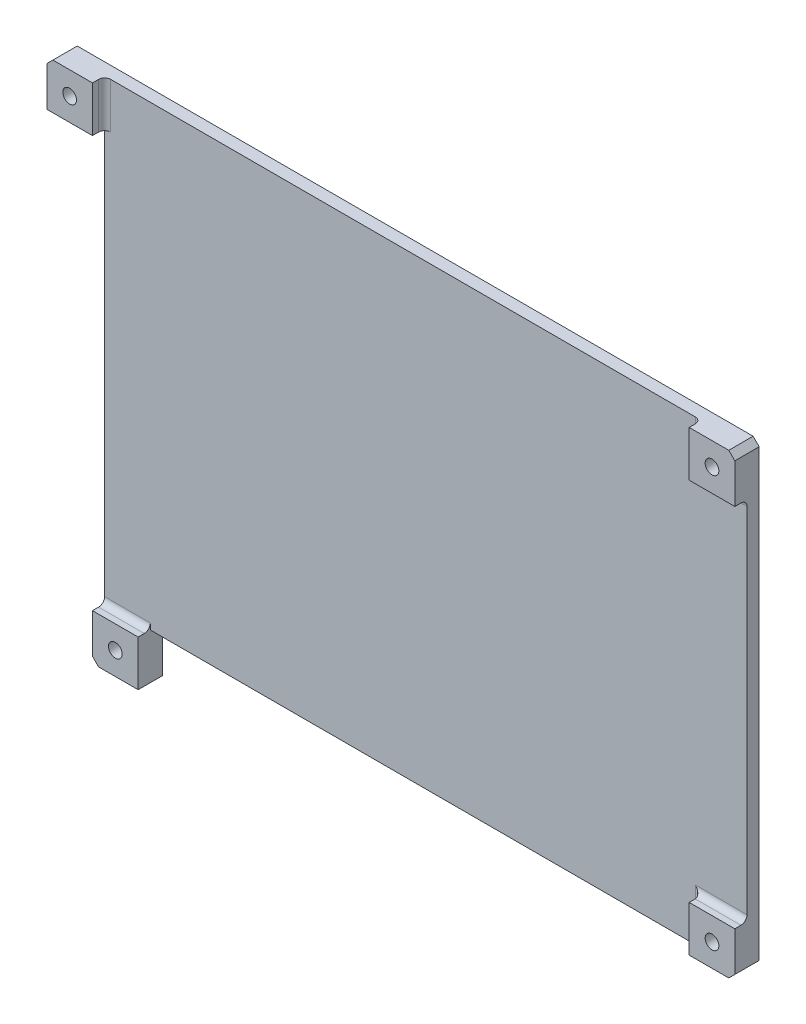
SolidWorks part; units mm, degrees
ref_plane "Front Plane" through (0, 0, 0) normal (0, 0, 1) x (1, 0, 0)
ref_plane "Top Plane" through (0, 0, 0) normal (0, 1, 0) x (1, 0, 0)
ref_plane "Right Plane" through (0, 0, 0) normal (1, 0, 0) x (0, 0, -1)
sketch "Sketch1" plane through (0, 0, 0) normal (0, 0, 1) x (1, 0, 0)
  line L1 (-43.4412, 24.5025) -> (62.0588, 24.5025)
  line L2 (-43.4412, 24.5025) -> (-43.4412, -50.5575)
  line L3 (-43.4412, -50.5575) -> (62.0588, -50.5575)
  line L4 (62.0588, 24.5025) -> (62.0588, -50.5575)
  dimension "D1" = 105.5
  dimension "D2" = 75.06
extrude "Boss-Extrude1" add sketch "Sketch1" along normal blind 2
sketch "Sketch2" plane through (0, 0, 2) normal (0, 0, 1) x (1, 0, 0)
  line L0 (-43.4412, -13.0275) -> (62.0588, -13.0275) construction
  line L1 (-43.4412, 24.5025) -> (-43.4412, -50.5575) construction
  line L2 (62.0588, -50.5575) -> (62.0588, 24.5025) construction
  line L3 (54.5588, -43.0575) -> (62.0588, -43.0575)
  line L4 (54.5588, 24.5025) -> (62.0588, 24.5025)
  line L5 (54.5588, 24.5025) -> (54.5588, 17.0025)
  line L6 (54.5588, 17.0025) -> (62.0588, 17.0025)
  line L7 (62.0588, 24.5025) -> (62.0588, 17.0025)
  line L8 (62.0588, -50.5575) -> (62.0588, -43.0575)
  line L9 (54.5588, -50.5575) -> (62.0588, -50.5575)
  line L10 (54.5588, -50.5575) -> (54.5588, -43.0575)
  circle A0 centre (58.3088, 20.7525) radius 1.125
  point P12 (0, 0)
  dimension "D1" = 2.25
  dimension "D4" = 3.75
  dimension "D5" = 3.75
  dimension "D2" = 7.5
  dimension "D3" = 7.5
extrude "Boss-Extrude2" add sketch "Sketch2" along normal blind 2
sketch "Sketch3" plane through (0, 0, 2) normal (0, 0, 1) x (1, 0, 0)
  circle A0 centre (58.3088, 20.7525) radius 1.125
  circle A1 centre (58.3088, 20.7525) radius 1.125 construction
  circle A2 centre (58.3088, 20.7525) radius 1.125 construction
extrude "Cut-Extrude1" cut sketch "Sketch3" against normal blind 4
sketch "Sketch4" plane through (0, 0, 4) normal (0, 0, 1) x (1, 0, 0)
  line L0 (62.0588, -43.0575) -> (54.5588, -43.0575) construction
  line L1 (54.5588, -43.0575) -> (54.5588, -50.5575) construction
  circle A0 centre (58.3088, -46.8075) radius 1.125
  dimension "D1" = 2.25
  dimension "D2" = 3.75
  dimension "D3" = 3.75
extrude "Cut-Extrude2" cut sketch "Sketch4" against normal blind 4
sketch "Sketch5" plane through (0, 0, 2) normal (0, 0, 1) x (1, 0, 0)
  line L1 (-50.9412, 24.5025) -> (-43.4412, 24.5025)
  line L2 (-50.9412, 24.5025) -> (-50.9412, 17.0025)
  line L3 (-50.9412, 17.0025) -> (-43.4412, 17.0025)
  line L4 (-43.4412, 24.5025) -> (-43.4412, 17.0025)
  point P4 (0, 0)
  dimension "D1" = 7.5
  dimension "D2" = 7.5
extrude "Boss-Extrude3" add sketch "Sketch5" along normal mid plane 4
sketch "Sketch6" plane through (0, 0, 4) normal (0, 0, 1) x (1, 0, 0)
  line L0 (-43.4412, 24.5025) -> (-50.9412, 24.5025) construction
  line L1 (-50.9412, 24.5025) -> (-50.9412, 17.0025) construction
  circle A0 centre (-47.1912, 20.7525) radius 1.125
  dimension "D1" = 2.25
  dimension "D2" = 3.75
  dimension "D3" = 3.75
extrude "Cut-Extrude3" cut sketch "Sketch6" against normal blind 4
sketch "Sketch7" plane through (0, 0, 2) normal (0, 0, 1) x (1, 0, 0)
  line L1 (-35.9412, -58.0575) -> (-43.4412, -58.0575)
  line L2 (-35.9412, -58.0575) -> (-35.9412, -50.5575)
  line L3 (-35.9412, -50.5575) -> (-43.4412, -50.5575)
  line L4 (-43.4412, -58.0575) -> (-43.4412, -50.5575)
  point P4 (-14.8384, -6.9774)
  point P5 (0, 0)
  dimension "D1" = 7.5
  dimension "D2" = 7.5
extrude "Boss-Extrude4" add sketch "Sketch7" along normal mid plane 4
sketch "Sketch8" plane through (0, 0, 4) normal (0, 0, 1) x (1, 0, 0)
  line L1 (-43.4412, -58.0575) -> (-35.9412, -58.0575) construction
  line L2 (-35.9412, -58.0575) -> (-35.9412, -50.5575) construction
  circle A0 centre (-39.6912, -54.3075) radius 1.125
  dimension "D1" = 2.25
  dimension "D2" = 3.75
  dimension "D3" = 3.75
extrude "Cut-Extrude4" cut sketch "Sketch8" against normal blind 4
fillet "Fillet2" radius 1 2 edges at (-39.6912, -50.5575, 2) (-43.4412, 20.7525, 2)
fillet "Fillet3" radius 1 4 edges at (58.3088, 17.0025, 2) (54.5588, 20.7525, 2) (54.5588, -46.8075, 2) (58.3088, -43.0575, 2)
chamfer "Chamfer1" distance 1 angle 45 4 edges at (62.0588, 24.5025, 2) (62.0588, -50.5575, 2) (-43.4412, -58.0575, 2) (-50.9412, 24.5025, 2)
